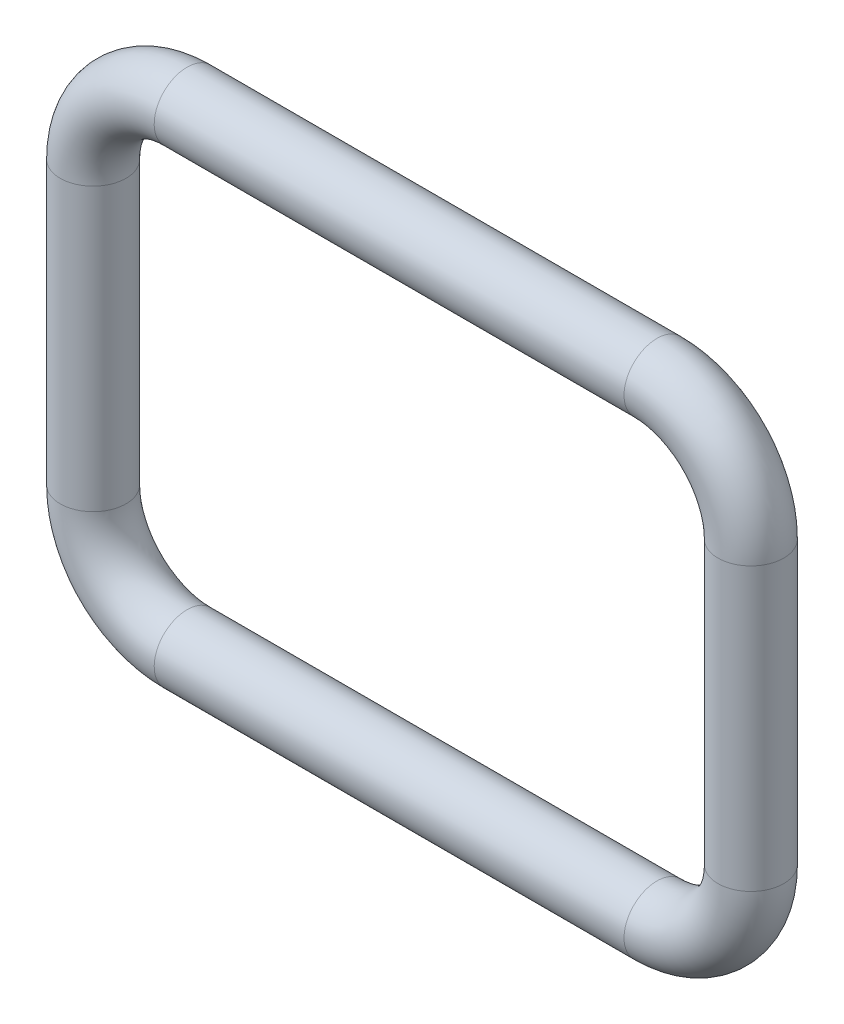
SolidWorks part; units mm, degrees
ref_plane "Front Plane" through (0, 0, 0) normal (0, 0, 1) x (1, 0, 0)
ref_plane "Top Plane" through (0, 0, 0) normal (0, 1, 0) x (1, 0, 0)
ref_plane "Right Plane" through (0, 0, 0) normal (1, 0, 0) x (0, 0, -1)
sketch "Sketch1" plane through (0, 0, 0) normal (0, 0, 1) x (1, 0, 0)
  line L0 (-3.6154, 4) -> (-3.6154, 1)
  line L1 (-2.6154, 0) -> (2.3846, 0)
  line L2 (3.3846, 1) -> (3.3846, 4)
  line L3 (-2.6154, 5) -> (2.3846, 5)
  arc A0 (2.3846, 0) -> (3.3846, 1) centre (2.3846, 1) ccw
  arc A1 (-3.6154, 1) -> (-2.6154, 0) centre (-2.6154, 1) ccw
  arc A2 (3.3846, 4) -> (2.3846, 5) centre (2.3846, 4) ccw
  arc A3 (-3.6154, 4) -> (-2.6154, 5) centre (-2.6154, 4) cw
  point P7 (3.3846, 0)
  point P10 (-3.6154, 0)
  point P15 (-3.6154, 5)
  dimension "D3" = 1
  dimension "D4" = 1
  dimension "D1" = 5
  dimension "D2" = 7
sweep "Sweep2" add path "Sketch1" circular profile diameter 0.7 parameters "D3"=0.7
